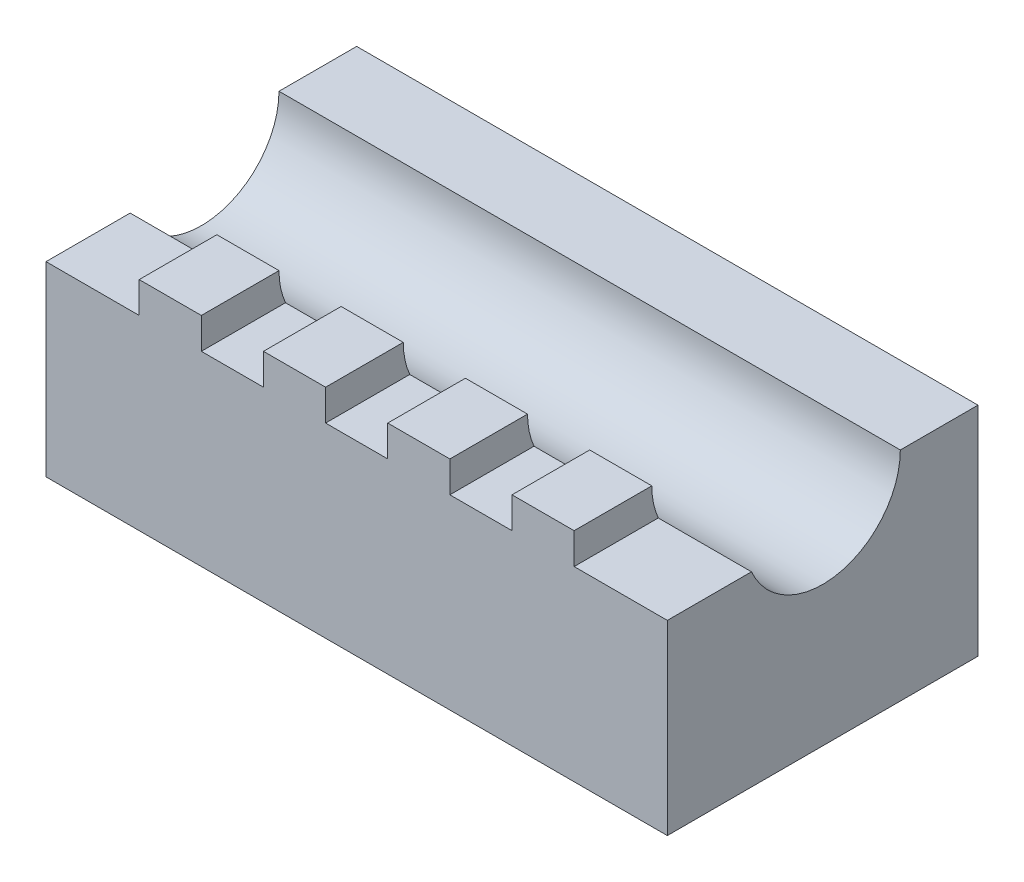
SolidWorks part; units mm, degrees
ref_plane "Front Plane" through (0, 0, 0) normal (0, 0, 1) x (1, 0, 0)
ref_plane "Top Plane" through (0, 0, 0) normal (0, 1, 0) x (1, 0, 0)
ref_plane "Right Plane" through (0, 0, 0) normal (1, 0, 0) x (0, 0, -1)
sketch "Sketch1" plane through (0, 0, 0) normal (0, 0, 1) x (1, 0, 0)
  line L1 (0, 0) -> (100, 0)
  line L2 (0, 0) -> (0, 35)
  line L3 (0, 35) -> (100, 35)
  line L4 (100, 0) -> (100, 35)
  dimension "D1" = 100
  dimension "D2" = 35
extrude "Boss-Extrude1" add sketch "Sketch1" along normal blind 50
sketch "Sketch4" plane through (100, 0, 0) normal (1, 0, 0) x (0, 0, -1)
  line L0 (-50, 35) -> (0, 35) construction
  circle A0 centre (-25, 35) radius 12.5
  dimension "D1" = 25
extrude "Cut-Extrude2" cut sketch "Sketch4" against normal blind 100
sketch "Sketch5" plane through (0, 0, 50) normal (0, 0, 1) x (1, 0, 0)
  line L0 (25, 35) -> (25, 30)
  line L1 (100, 35) -> (0, 35) construction
  line L2 (25, 30) -> (35, 30)
  line L3 (35, 30) -> (35, 35)
  line L4 (65, 35) -> (65, 30)
  line L5 (85, 35) -> (85, 30)
  line L6 (85, 30) -> (100, 30)
  line L7 (100, 30) -> (100, 35)
  line L11 (25, 35) -> (35, 35)
  line L12 (85, 35) -> (100, 35)
  line L13 (65, 30) -> (75, 30)
  line L14 (75, 35) -> (75, 30)
  line L16 (65, 35) -> (75, 35)
  line L21 (100, 0) -> (100, 35) construction
  line L23 (0, 35) -> (15, 35)
  line L24 (0, 35) -> (0, 30)
  line L25 (0, 30) -> (15, 30)
  line L26 (15, 35) -> (15, 30)
  line L27 (0, 35) -> (0, 0) construction
  line L29 (45, 35) -> (55, 35)
  line L30 (45, 35) -> (45, 30)
  line L31 (45, 30) -> (55, 30)
  line L32 (55, 35) -> (55, 30)
  line M11 (100, 35) -> (0, 35)
  dimension "D1" = 10
  dimension "D2" = 15
  dimension "D3" = 5
  dimension "D4" = 5
  dimension "D5" = 5
  dimension "D6" = 0
  dimension "D7" = 10
  dimension "D8" = 10
  dimension "D9" = 10
  dimension "D10" = 15
  dimension "D11" = 0
  dimension "D12" = 10
  dimension "D13" = 10
extrude "Cut-Extrude3" cut sketch "Sketch5" against normal blind 25 contours L26 L24 L25 M11 | L2 L3 L0 M11 | L14 L4 L13 M11 | L6 L7 L5 M11 | L32 L30 L31 M11
